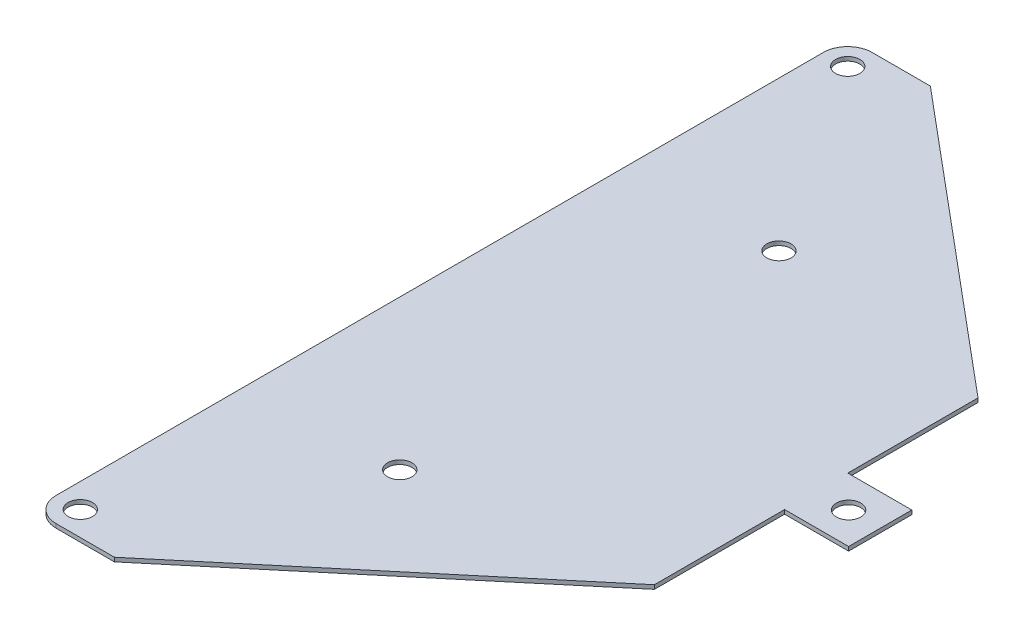
SolidWorks part; units mm, degrees
ref_plane "Front Plane" through (0, 0, 0) normal (0, 0, 1) x (1, 0, 0)
ref_plane "Top Plane" through (0, 0, 0) normal (0, 1, 0) x (1, 0, 0)
ref_plane "Right Plane" through (0, 0, 0) normal (1, 0, 0) x (0, 0, -1)
sketch "Croquis1" plane through (0, 0, 0) normal (0, 1, 0) x (1, 0, 0)
  line L0 (43.47, -43.46) -> (51.37, -43.46)
  line L1 (51.37, -43.46) -> (51.37, -51.26)
  line L2 (51.37, -51.26) -> (43.47, -51.26)
  line L4 (-3, -94.72) -> (-3, 0)
  line L6 (43.47, -43.46) -> (43.47, -27.39)
  line L7 (43.47, -27.39) -> (7.2, 3)
  line L8 (7.2, 3) -> (0, 3)
  line L9 (0, -97.72) -> (7.2, -97.72)
  line L10 (7.2, -97.72) -> (43.47, -67.33)
  line L11 (43.47, -67.33) -> (43.47, -51.26)
  circle A0 centre (0, 0) radius 1.5
  circle A1 centre (0, -94.72) radius 1.5
  circle A2 centre (47.47, -47.36) radius 1.5
  arc A4 (0, -97.72) -> (-3, -94.72) centre (0, -94.72) cw
  arc A5 (-3, 0) -> (0, 3) centre (0, 0) cw
  circle A6 centre (15.47, -23.96) radius 1.5
  circle A7 centre (15.47, -70.76) radius 1.5
  point P22 (-3, -47.36)
  dimension "D2" = 3
  dimension "D5" = 3
  dimension "D1" = 94.72
  dimension "D3" = 47.47
  dimension "D4" = 47.36
  dimension "D6" = 3.9
  dimension "D7" = 3.9
  dimension "D8" = 3.9
  dimension "D9" = 4
  dimension "D11" = 7.2
  dimension "D10" = 39.94
  dimension "D12" = 19.97
  dimension "D13" = 32
  dimension "D14" = 46.8
  dimension "D15" = 23.4
extrude "Saliente-Extruir1" add sketch "Croquis1" along normal blind 0.5
sketch "Croquis2" plane through (0, 0, 0) normal (0, -1, 0) x (1, 0, 0)
  circle A0 centre (15.47, 70.76) radius 2.75
  circle A1 centre (15.47, 23.96) radius 2.75
  dimension "D1" = 5.5
equation "\"D4@Croquis1\"=\"D1@Croquis1\"/2"
equation "\"D12@Croquis1\"=\"D10@Croquis1\"/2"
equation "\"D15@Croquis1\"=\"D14@Croquis1\"/2"
